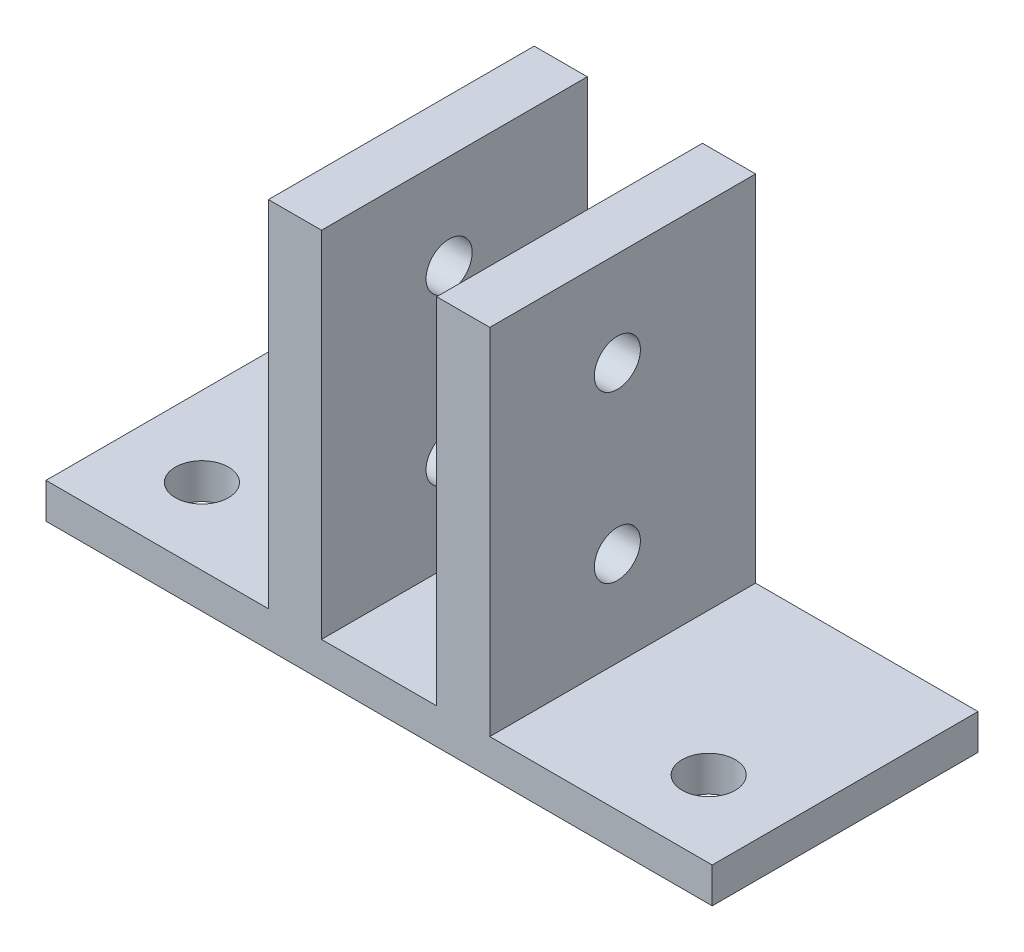
SolidWorks part; units mm, degrees
ref_plane "Alzado" through (0, 0, 0) normal (0, 0, 1) x (1, 0, 0)
ref_plane "Planta" through (0, 0, 0) normal (0, 1, 0) x (1, 0, 0)
ref_plane "Vista lateral" through (0, 0, 0) normal (1, 0, 0) x (0, 0, -1)
sketch "Croquis1" plane through (0, 0, 0) normal (0, 1, 0) x (1, 0, 0)
  line L0 (18.8, 7.5) -> (18.8, 0) construction
  line L2 (18.8, -7.5) -> (18.8, 7.5)
  line L3 (18.8, 7.5) -> (-18.8, 7.5)
  line L4 (-18.8, -7.5) -> (-18.8, 7.5)
  line L5 (18.8, -7.5) -> (-18.8, 7.5) construction
  line L6 (18.8, 7.5) -> (-18.8, -7.5) construction
  line L7 (14.3, -3.2) -> (14.3, -7.5) construction
  line L8 (0, 7.5) -> (0, -7.5) construction
  line L9 (-18.8, -7.5) -> (18.8, -7.5)
  line L10 (0, 7.5) -> (-3.25, 7.5) construction
  line L11 (14.3, -3.2) -> (18.8, -3.2) construction
  circle A0 centre (14.3, -3.2) radius 1.5
  circle A2 centre (-14.3, -3.2) radius 1.5
  point P0 (0, 0)
  dimension "D3" = 3
  dimension "D1" = 37.6
  dimension "D2" = 15
extrude "Saliente-Extruir1" add sketch "Croquis1" along normal blind 2
sketch "Croquis2" plane through (0, 2, 0) normal (0, 1, 0) x (1, 0, 0)
  line L0 (0, 7.5) -> (-3.25, 7.5) construction
  line L1 (18.8, 7.5) -> (-18.8, 7.5) construction
  line L2 (-3.25, 7.5) -> (-3.25, -7.5)
  line L3 (-18.8, -7.5) -> (18.8, -7.5) construction
  line L4 (-3.25, -7.5) -> (-6.2474, -7.5)
  line L5 (-6.2474, -7.5) -> (-6.2474, 7.5)
  line L6 (-6.2474, 7.5) -> (-3.25, 7.5)
  line L7 (0, 7.5) -> (0, -7.5) construction
  line L8 (6.2474, -7.5) -> (6.2474, 7.5)
  line L9 (3.25, -7.5) -> (6.2474, -7.5)
  line L10 (3.25, 7.5) -> (3.25, -7.5)
  line L11 (6.2474, 7.5) -> (3.25, 7.5)
extrude "Saliente-Extruir2" add sketch "Croquis2" along normal blind 20
sketch "Croquis3" plane through (-6.2474, 0, 0) normal (-1, 0, 0) x (0, 0, 1)
  line L0 (7.5, 22) -> (-2.5, 22) construction
  line L1 (-7.5, 22) -> (7.5, 22) construction
  line L2 (-2.5, 22) -> (-2.5, 2) construction
  line L3 (-7.5, 2) -> (7.5, 2) construction
  line L4 (-2.5, 2) -> (7.5, 2) construction
  line L5 (-2.5, 22) -> (-2.5, 16.6697) construction
  line L6 (-2.5, 16.6697) -> (0.3, 16.6697) construction
  line L7 (-2.5, 12) -> (7.5, 12) construction
  line L8 (7.5, 22) -> (7.5, 2) construction
  circle A0 centre (0.3, 16.6697) radius 1.3
  circle A1 centre (0.3, 7.3303) radius 1.3
  dimension "D1" = 2.6
extrude "Cortar-Extruir1" cut sketch "Croquis3" against normal blind 20
